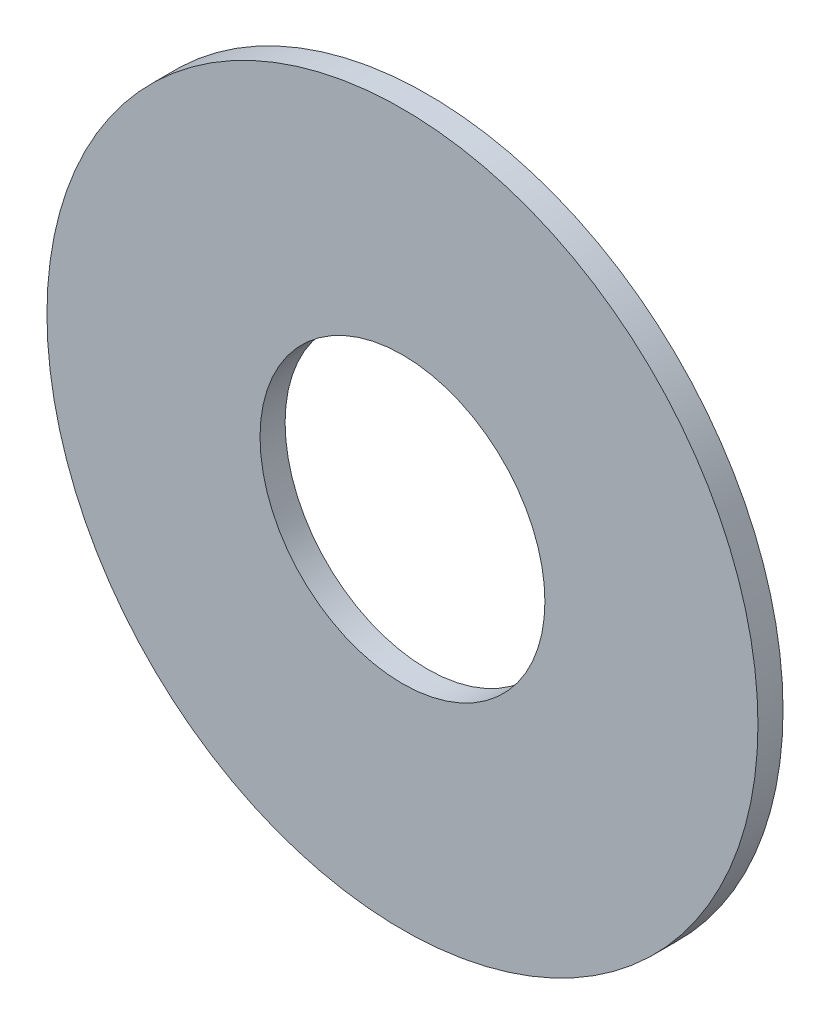
SolidWorks part; units mm, degrees
ref_plane "Front Plane" through (0, 0, 0) normal (0, 0, 1) x (1, 0, 0)
ref_plane "Top Plane" through (0, 0, 0) normal (0, 1, 0) x (1, 0, 0)
ref_plane "Right Plane" through (0, 0, 0) normal (1, 0, 0) x (0, 0, -1)
sketch "Sketch2" plane through (0, 0, 0) normal (0, 0, 1) x (1, 0, 0)
  circle A0 centre (0, 0) radius 11.2522
  circle A1 centre (0, 0) radius 4.5085
  dimension "D1" = 22.5044
  dimension "D2" = 9.017
extrude "Boss-Extrude1" add sketch "Sketch2" along normal blind 0.7937
